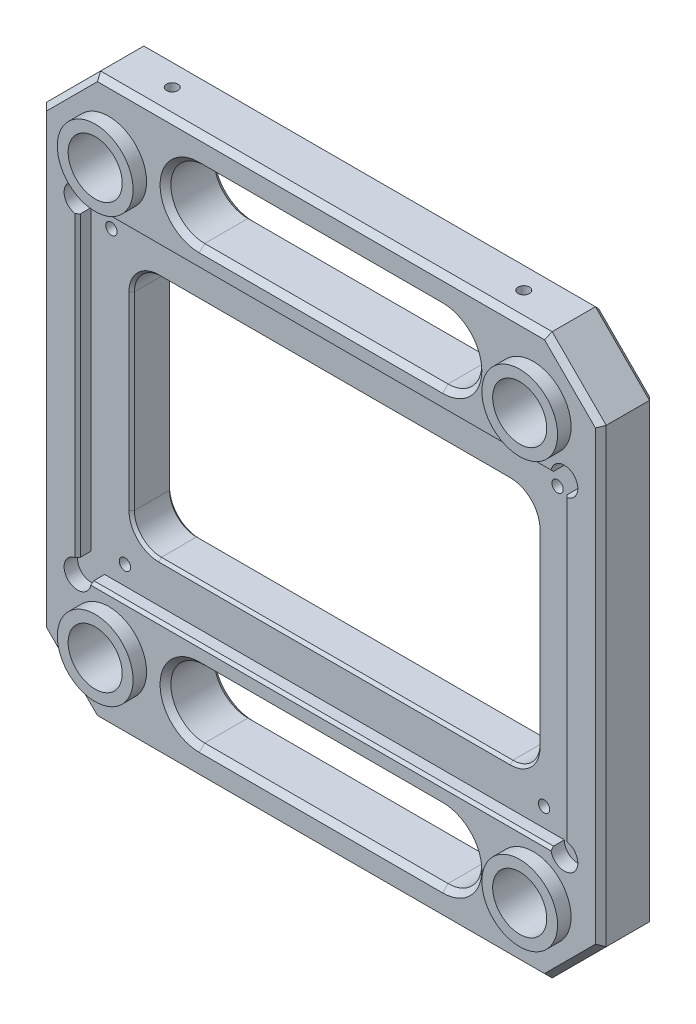
SolidWorks part; units mm, degrees
ref_plane "前视基准面" through (0, 0, 0) normal (0, 0, 1) x (1, 0, 0)
ref_plane "上视基准面" through (0, 0, 0) normal (0, 1, 0) x (1, 0, 0)
ref_plane "右视基准面" through (0, 0, 0) normal (1, 0, 0) x (0, 0, -1)
sketch "草图1" plane through (0, 0, 0) normal (0, 0, 1) x (1, 0, 0)
  line L1 (-103.5, 103.5) -> (103.5, 103.5)
  line L2 (-103.5, 103.5) -> (-103.5, -103.5)
  line L3 (-103.5, -103.5) -> (103.5, -103.5)
  line L4 (103.5, 103.5) -> (103.5, -103.5)
  line L5 (-103.5, 103.5) -> (103.5, -103.5) construction
  line L6 (-103.5, -103.5) -> (103.5, 103.5) construction
  point P0 (0, 0)
  dimension "D1" = 207
  dimension "D2" = 207
extrude "凸台-拉伸1" add sketch "草图1" along normal blind 20
sketch "草图4" plane through (0, 0, 20) normal (0, 0, 1) x (1, 0, 0)
  line L1 (-78.5, -78.5) -> (78.5, -78.5) construction
  line L2 (-78.5, -78.5) -> (-78.5, 78.5) construction
  line L3 (-78.5, 78.5) -> (78.5, 78.5) construction
  line L4 (78.5, -78.5) -> (78.5, 78.5) construction
  line L5 (-78.5, -78.5) -> (78.5, 78.5) construction
  line L6 (-78.5, 78.5) -> (78.5, -78.5) construction
  circle A0 centre (-78.5, -78.5) radius 14
  circle A1 centre (-78.5, 78.5) radius 14
  circle A2 centre (78.5, 78.5) radius 14
  circle A3 centre (78.5, -78.5) radius 14
  point P0 (0, 0)
  dimension "D2" = 28
  dimension "D1" = 157
extrude "凸台-拉伸2" add sketch "草图4" along normal blind 5
hole_wizard "打孔尺寸(%根据)内六角圆柱头螺钉的类型1" positions "草图7" profile "草图8" counterbore size "M12" standard "GB"
sketch "草图7" plane through (0, 0, 25) normal (0, 0, 1) x (1, 0, 0)
  point P0 (-78.5, -78.5)
  point P3 (-78.5, 78.5)
  point P6 (78.5, 78.5)
  point P9 (78.5, -78.5)
sketch "草图8" plane through (-78.5, -78.5, 25) normal (1, 0, 0) x (0, -1, 0)
  line L0 (0, 0) -> (0, 61.0558)
  line L1 (0, 61.0558) -> (6.75, 57)
  line L2 (6.75, 57) -> (6.75, 18)
  line L3 (6.75, 18) -> (10, 18)
  line L4 (10, 18) -> (10, 0)
  line L5 (10, 0) -> (0, 0)
  line L10 (0, 61.0558) -> (-6.75, 57) construction
  line L11 (0, -6.35) -> (0, 107.95) construction
  dimension "孔直径" = 13.5
  dimension "孔深度" = 57
  dimension "柱形沉头孔直径" = 20
  dimension "柱形沉头孔深度" = 18
  dimension "导头角度" = 118
chamfer "倒角2" distance 20 angle 45 4 edges at (103.5, 103.5, 10) (-103.5, 103.5, 10) (-103.5, -103.5, 10) (103.5, -103.5, 10)
sketch "草图9" plane through (0, 0, 20) normal (0, 0, 1) x (1, 0, 0)
  line L1 (90, 60) -> (-90, 60)
  line L2 (90, 60) -> (90, -60)
  line L3 (90, -60) -> (-90, -60)
  line L4 (-90, 60) -> (-90, -60)
  line L5 (90, 60) -> (-90, -60) construction
  line L6 (90, -60) -> (-90, 60) construction
  point P0 (0, 0)
  dimension "D1" = 180
  dimension "D2" = 120
extrude "切除-拉伸1" cut sketch "草图9" against normal blind 5
sketch "草图10" plane through (0, 0, 20) normal (0, 0, 1) x (1, 0, 0)
  circle A0 centre (90, -60) radius 5
  circle A1 centre (-90, -60) radius 5
  circle A2 centre (90, 60) radius 5
  circle A3 centre (-90, 60) radius 5
  dimension "D1" = 10
extrude "切除-拉伸2" cut sketch "草图10" against normal up to surface (5 mm away) up to face at (0, 0, 15)
sketch "草图11" plane through (0, 0, 20) normal (0, 0, 1) x (1, 0, 0)
  line L0 (0, 80) -> (0, -80) construction
  line L1 (45, -80) -> (-45, -80) construction
  line L2 (45, -92.5) -> (-45, -92.5)
  line L3 (45, -67.5) -> (-45, -67.5)
  line L4 (45, 80) -> (-45, 80) construction
  line L5 (45, 67.5) -> (-45, 67.5)
  line L6 (45, 92.5) -> (-45, 92.5)
  arc A0 (45, -92.5) -> (45, -67.5) centre (45, -80) ccw
  arc A1 (-45, -67.5) -> (-45, -92.5) centre (-45, -80) ccw
  arc A2 (45, 67.5) -> (45, 92.5) centre (45, 80) ccw
  arc A3 (-45, 92.5) -> (-45, 67.5) centre (-45, 80) ccw
  point P4 (0, 0)
  point P7 (0, -80)
  point P14 (0, 80)
  dimension "D1" = 160
  dimension "D2" = 25
  dimension "D3" = 90
extrude "切除-拉伸3" cut sketch "草图11" against normal through all
chamfer "倒角1" distance 2 angle 45 32 edges at (0, 103.5, 20) (-93.5, 93.5, 20) (93.5, 93.5, 20) (-103.5, 0, 20) (103.5, 0, 20) (-93.5, -93.5, 20) (93.5, -93.5, 20) (0, -103.5, 20) (0, 103.5, 0) (-93.5, 93.5, 0) (93.5, 93.5, 0) (-103.5, 0, 0) (103.5, 0, 0) (-93.5, -93.5, 0) (93.5, -93.5, 0) (0, -103.5, 0) (0, 92.5, 20) (-57.5, 80, 20) (57.5, 80, 20) (0, 67.5, 20) (0, 92.5, 0) (-57.5, 80, 0) (57.5, 80, 0) (0, 67.5, 0) (0, -67.5, 20) (-57.5, -80, 20) (57.5, -80, 20) (0, -92.5, 20) (0, -67.5, 0) (-57.5, -80, 0) (57.5, -80, 0) (0, -92.5, 0)
sketch "草图12" plane through (0, 0, 15) normal (0, 0, 1) x (1, 0, 0)
  line L0 (-90, 55) -> (-90, -55) construction
  line L1 (75, 45) -> (-75, 45)
  line L2 (75, 45) -> (75, -45)
  line L3 (75, -45) -> (-75, -45)
  line L4 (-75, 45) -> (-75, -45)
  line L5 (75, 45) -> (-75, -45) construction
  line L6 (75, -45) -> (-75, 45) construction
  line L7 (-85, -60) -> (85, -60) construction
  point P0 (0, 0)
  dimension "D1" = 15
  dimension "D2" = 15
extrude "切除-拉伸4" cut sketch "草图12" against normal through all
fillet "圆角1" radius 10 4 edges at (75, 45, 7.5) (-75, 45, 7.5) (-75, -45, 7.5) (75, -45, 7.5)
chamfer "倒角3" distance 1 angle 45 20 edges at (0, -45, 0) (72.0711, -42.0711, 0) (-72.0711, -42.0711, 0) (75, 0, 0) (-75, 0, 0) (72.0711, 42.0711, 0) (-72.0711, 42.0711, 0) (0, 45, 0) (0, -45, 15) (72.0711, -42.0711, 15) (-72.0711, -42.0711, 15) (75, 0, 15) (-75, 0, 15) (72.0711, 42.0711, 15) (-72.0711, 42.0711, 15) (0, 45, 15) (0, -60, 20) (90, 0, 20) (0, 60, 20) (-90, 0, 20)
hole_wizard "M5 螺纹孔1" positions "草图13" profile "草图14" tap size "M5" standard "GB"
sketch "草图13" plane through (0, 0, 15) normal (0, 0, 1) x (1, 0, 0)
  point P0 (77.5, -53)
  point P3 (-77.5, -53)
  point P6 (-82.5, 52)
  point P9 (82.5, 52)
sketch "草图14" plane through (77.5, -53, 15) normal (1, 0, 0) x (0, -1, 0)
  line L0 (0, 0) -> (0, 13.6618)
  line L1 (0, 13.6618) -> (2.1, 12.4)
  line L2 (2.1, 12.4) -> (2.1, 0)
  line L5 (2.1, 0) -> (0, 0)
  line L10 (0, 13.6618) -> (-2.1, 12.4) construction
  line L11 (0, -6.35) -> (0, 107.95) construction
  dimension "螺纹孔钻头直径" = 4.2
  dimension "螺纹孔钻头深度" = 12.4
  dimension "导头角度" = 118
cosmetic thread "孔螺蚊线1" parameters "D1"=10, "D2"=5
cosmetic thread "孔螺蚊线2" parameters "D1"=10, "D2"=5
cosmetic thread "孔螺蚊线3" parameters "D1"=10, "D2"=5
cosmetic thread "孔螺蚊线4" parameters "D1"=10, "D2"=5
hole_wizard "M5 螺纹孔2" positions "草图20" profile "草图21" tap size "M5" standard "GB"
sketch "草图20" plane through (0, 103.5, 0) normal (0, 1, 0) x (1, 0, 0)
  line L0 (0, -20) -> (0, 0) construction
  line L1 (82.6716, -20) -> (-82.6716, -20) construction
  line L3 (65, -10) -> (-65, -10) construction
  point P7 (65, -10)
  point P8 (-65, -10)
  point P11 (0, -10)
  point P12 (0, -10)
  dimension "D1" = 130
sketch "草图21" plane through (-65, 103.5, 10) normal (1, 0, 0) x (0, 0, 1)
  line L0 (0, 0) -> (0, 13.6618)
  line L1 (0, 13.6618) -> (2.1, 12.4)
  line L2 (2.1, 12.4) -> (2.1, 0)
  line L5 (2.1, 0) -> (0, 0)
  line L10 (0, 13.6618) -> (-2.1, 12.4) construction
  line L11 (0, -6.35) -> (0, 107.95) construction
  dimension "螺纹孔钻头直径" = 4.2
  dimension "螺纹孔钻头深度" = 12.4
  dimension "导头角度" = 118
cosmetic thread "孔螺蚊线5" parameters "D1"=10, "D2"=5
cosmetic thread "孔螺蚊线6" parameters "D1"=10, "D2"=5
